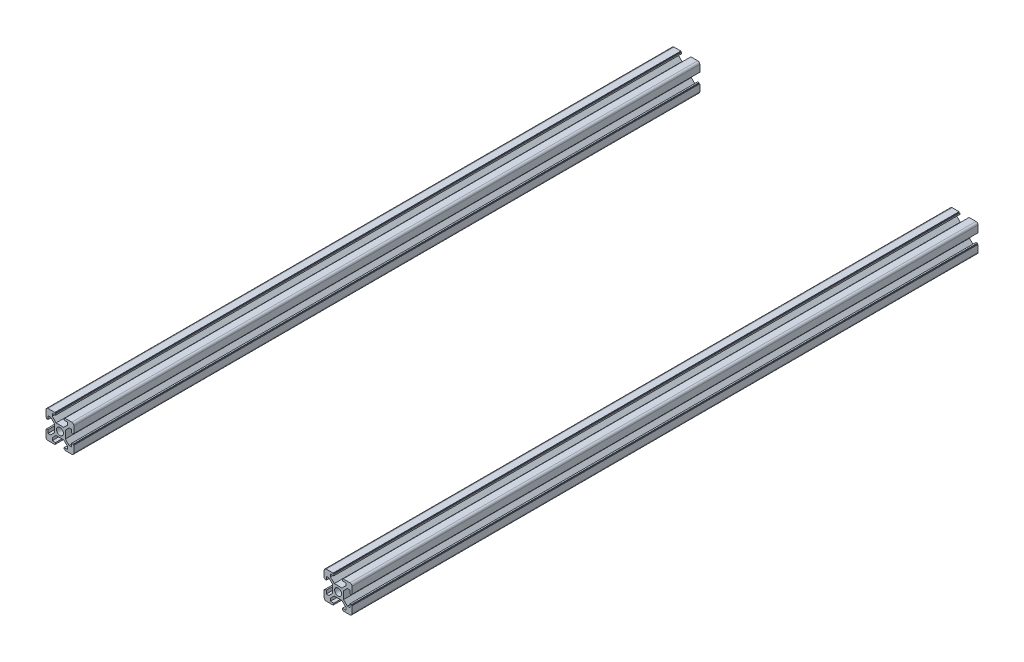
SolidWorks part; units mm, degrees
ref_plane "前视基准面" through (0, 0, 0) normal (0, 0, 1) x (1, 0, 0)
ref_plane "上视基准面" through (0, 0, 0) normal (0, 1, 0) x (1, 0, 0)
ref_plane "右视基准面" through (0, 0, 0) normal (1, 0, 0) x (0, 0, -1)
sketch3d "3D草图1"
  line L0 (0, 0, 0) -> (0, 0, -450)
  line L1 (0, 0, -450) -> (200, 0, -450)
  line L2 (200, 0, -450) -> (200, 0, 0)
  line L3 (200, 0, 0) -> (0, 0, 0)
  dimension "D1" = 450
  dimension "D2" = 450
  dimension "D3" = 200
other "工业铝型材 20 X 20 X R1.5(1)"
ref_plane "基准面1" through (0, 0, 0) normal (0, 0, -1) x (1, 0, 0)
sketch "Sketch1" plane through (0, 0, 0) normal (0, 0, -1) x (1, 0, 0)
  line L0 (-3.6, 10) -> (-3.6, 9.5)
  line L1 (-3.6, 9.5) -> (-3.1, 9.5)
  line L2 (-3.1, 9.5) -> (-3.1, 8.5)
  line L3 (-3.1, 8.5) -> (-5.5, 8.5)
  line L4 (-8.5, -10) -> (-3.6, -10)
  line L5 (-10, -8.5) -> (-10, -3.6)
  line L6 (8.5, 10) -> (3.6, 10)
  line L7 (10, 8.5) -> (10, 3.6)
  line L8 (0, 14.8756) -> (0, 0) construction
  line L9 (0, 0) -> (14.1675, 0) construction
  line L10 (-5.5, 8.5) -> (-5.5, 6.65)
  line L11 (-5.5, 6.65) -> (-2.75, 3.9)
  line L12 (-2.75, 3.9) -> (2.75, 3.9)
  line L13 (5.5, 6.65) -> (2.75, 3.9)
  line L14 (5.5, 8.5) -> (5.5, 6.65)
  line L15 (3.1, 8.5) -> (5.5, 8.5)
  line L16 (3.1, 9.5) -> (3.1, 8.5)
  line L17 (3.6, 9.5) -> (3.1, 9.5)
  line L18 (3.6, 10) -> (3.6, 9.5)
  line L19 (-3.6, 10) -> (-8.5, 10)
  line L20 (10, 3.6) -> (9.5, 3.6)
  line L21 (9.5, 3.6) -> (9.5, 3.1)
  line L22 (9.5, 3.1) -> (8.5, 3.1)
  line L23 (8.5, 3.1) -> (8.5, 5.5)
  line L24 (8.5, 5.5) -> (6.65, 5.5)
  line L25 (6.65, 5.5) -> (3.9, 2.75)
  line L26 (3.9, 2.75) -> (3.9, -2.75)
  line L27 (6.65, -5.5) -> (3.9, -2.75)
  line L28 (8.5, -5.5) -> (6.65, -5.5)
  line L29 (8.5, -3.1) -> (8.5, -5.5)
  line L30 (9.5, -3.1) -> (8.5, -3.1)
  line L31 (9.5, -3.6) -> (9.5, -3.1)
  line L32 (10, -3.6) -> (9.5, -3.6)
  line L33 (3.6, -10) -> (3.6, -9.5)
  line L34 (3.6, -9.5) -> (3.1, -9.5)
  line L35 (3.1, -9.5) -> (3.1, -8.5)
  line L36 (3.1, -8.5) -> (5.5, -8.5)
  line L37 (5.5, -8.5) -> (5.5, -6.65)
  line L38 (5.5, -6.65) -> (2.75, -3.9)
  line L39 (2.75, -3.9) -> (-2.75, -3.9)
  line L40 (-5.5, -6.65) -> (-2.75, -3.9)
  line L41 (-5.5, -8.5) -> (-5.5, -6.65)
  line L42 (-3.1, -8.5) -> (-5.5, -8.5)
  line L43 (-3.1, -9.5) -> (-3.1, -8.5)
  line L44 (-3.6, -9.5) -> (-3.1, -9.5)
  line L45 (-3.6, -10) -> (-3.6, -9.5)
  line L46 (-10, -3.6) -> (-9.5, -3.6)
  line L47 (-9.5, -3.6) -> (-9.5, -3.1)
  line L48 (-9.5, -3.1) -> (-8.5, -3.1)
  line L49 (-8.5, -3.1) -> (-8.5, -5.5)
  line L50 (-8.5, -5.5) -> (-6.65, -5.5)
  line L51 (-6.65, -5.5) -> (-3.9, -2.75)
  line L52 (-3.9, -2.75) -> (-3.9, 2.75)
  line L53 (-6.65, 5.5) -> (-3.9, 2.75)
  line L54 (-8.5, 5.5) -> (-6.65, 5.5)
  line L55 (-8.5, 3.1) -> (-8.5, 5.5)
  line L56 (-9.5, 3.1) -> (-8.5, 3.1)
  line L57 (-9.5, 3.6) -> (-9.5, 3.1)
  line L58 (-10, 3.6) -> (-9.5, 3.6)
  line L59 (3.6, -10) -> (8.5, -10)
  line L60 (-10, 3.6) -> (-10, 8.5)
  line L61 (10, -3.6) -> (10, -8.5)
  circle A0 centre (0, 0) radius 2.5
  arc A1 (-10, 8.5) -> (-8.5, 10) centre (-8.5, 8.5) cw
  arc A2 (10, 8.5) -> (8.5, 10) centre (8.5, 8.5) ccw
  arc A3 (-8.5, -10) -> (-10, -8.5) centre (-8.5, -8.5) cw
  arc A4 (8.5, -10) -> (10, -8.5) centre (8.5, -8.5) ccw
  point P0 (-10, 0)
  point P1 (10, 0)
  point P2 (0, 10)
  point P3 (0, -10)
  point P4 (0, 0)
  point P5 (-10, -10)
  point P6 (10, -10)
  point P7 (10, 10)
  point P8 (-10, 10)
  point P13 (0, 0)
  point P36 (-10, 10)
  point P39 (10, 10)
  dimension "D1" = 11
  dimension "D2" = 20
  dimension "D3" = 6.2
  dimension "D4" = 7.2
  dimension "D5" = 6.1
  dimension "D6" = 5
  dimension "D7" = 1.5
  dimension "D8" = 45
  dimension "D9" = 0.5
  dimension "D10" = 1
  dimension "D11" = 5.5
